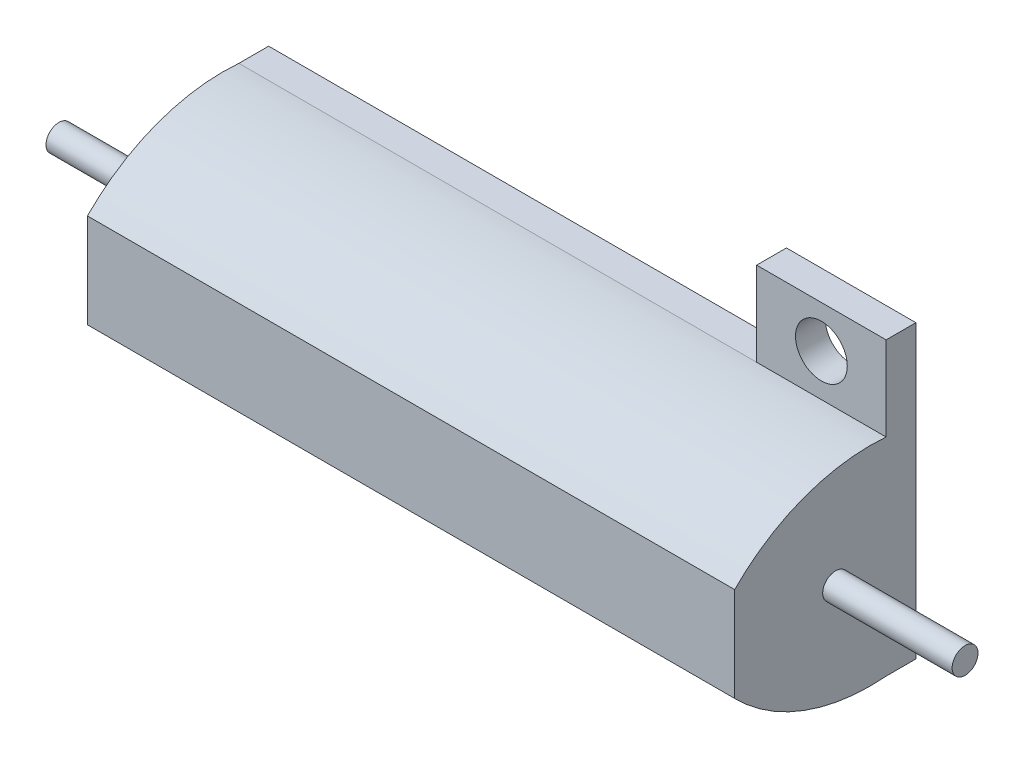
SolidWorks part; units mm, degrees
ref_plane "前视基准面" through (0, 0, 0) normal (0, 0, 1) x (1, 0, 0)
ref_plane "上视基准面" through (0, 0, 0) normal (0, 1, 0) x (1, 0, 0)
ref_plane "右视基准面" through (0, 0, 0) normal (1, 0, 0) x (0, 0, -1)
sketch "草图1" plane through (0, 0, 0) normal (0, 0, 1) x (1, 0, 0)
  line L0 (0, 21.2759) -> (0, -16.314) construction
  line L1 (-25, 8) -> (25, 8)
  line L2 (-25, 8) -> (-25, -8)
  line L3 (-25, -8) -> (25, -8)
  line L4 (25, 8) -> (25, -8)
  line L5 (-25.4038, 0) -> (20.5157, 0) construction
  dimension "D1" = 50
  dimension "D2" = 16
extrude "拉伸1" add sketch "草图1" along normal blind 2.3
sketch "草图2" plane through (0, 0, 0) normal (0, 0, -1) x (-1, 0, 0)
  line L0 (-20, 19.1659) -> (-20, 5.2783) construction
  line L1 (25, -8) -> (15, -8)
  line L2 (25, -8) -> (25, -14.5)
  line L3 (25, -14.5) -> (15, -14.5)
  line L4 (15, -8) -> (15, -14.5)
  line L5 (-25, 8) -> (-15, 8)
  line L6 (-25, 8) -> (-25, 14.5)
  line L7 (-25, 14.5) -> (-15, 14.5)
  line L8 (-15, 8) -> (-15, 14.5)
  line L9 (-10.0104, 11.25) -> (-26.738, 11.25) construction
  line L10 (1.9413, -11.25) -> (30.7177, -11.25) construction
  line L11 (20, -6.7597) -> (20, -18.109) construction
  line L12 (0, 19.1659) -> (0, -16.4237) construction
  circle A0 centre (-20, 11.25) radius 2
  circle A1 centre (20, -11.25) radius 2
  dimension "D5" = 4
  dimension "D6" = 4
  dimension "D1" = 6.5
  dimension "D2" = 10
  dimension "D3" = 6.5
  dimension "D4" = 10
  dimension "D7" = 40
  dimension "D8" = 20
extrude "拉伸2" add sketch "草图2" against normal up to surface (2.3 mm away) up to face at (0, 0, 2.3)
sketch "草图4" plane through (25, 0, 0) normal (1, 0, 0) x (0, 0, -1)
  line L0 (-2.3, -8) -> (-2.3, 8)
  line L1 (8.3066, 0) -> (-17.5153, 0) construction
  line L2 (-14, -3.6418) -> (-14, 3.6418)
  line L3 (0, -8) -> (0, 14.5) construction
  arc A0 (-2.3, -8) -> (-14, -3.6418) centre (-3.515, 6.6223) cw
  arc A1 (-2.3, 8) -> (-14, 3.6418) centre (-3.515, -6.6223) ccw
  point P14 (-14, 0)
  dimension "D1" = 14
extrude "拉伸3" add sketch "草图4" against normal up to surface (50 mm away) up to face at (-25, -3.25, 1.15)
sketch "草图5" plane through (0, 0, 0) normal (1, 0, 0) x (0, 0, -1)
  line L0 (2.7647, 0) -> (-20.739, 0) construction
  line L1 (0, -8) -> (0, 14.5) construction
  circle A0 centre (-6.2, 0) radius 1
  dimension "D2" = 2
  dimension "D1" = 6.2
extrude "拉伸4" add sketch "草图5" along normal offset from surface 10 and the other way offset from surface (35 mm away) 10 up to face at (25, 2.6604, 4.2195) offset beyond the face yes other way up to face at (-25, -2.6604, 4.2195)
